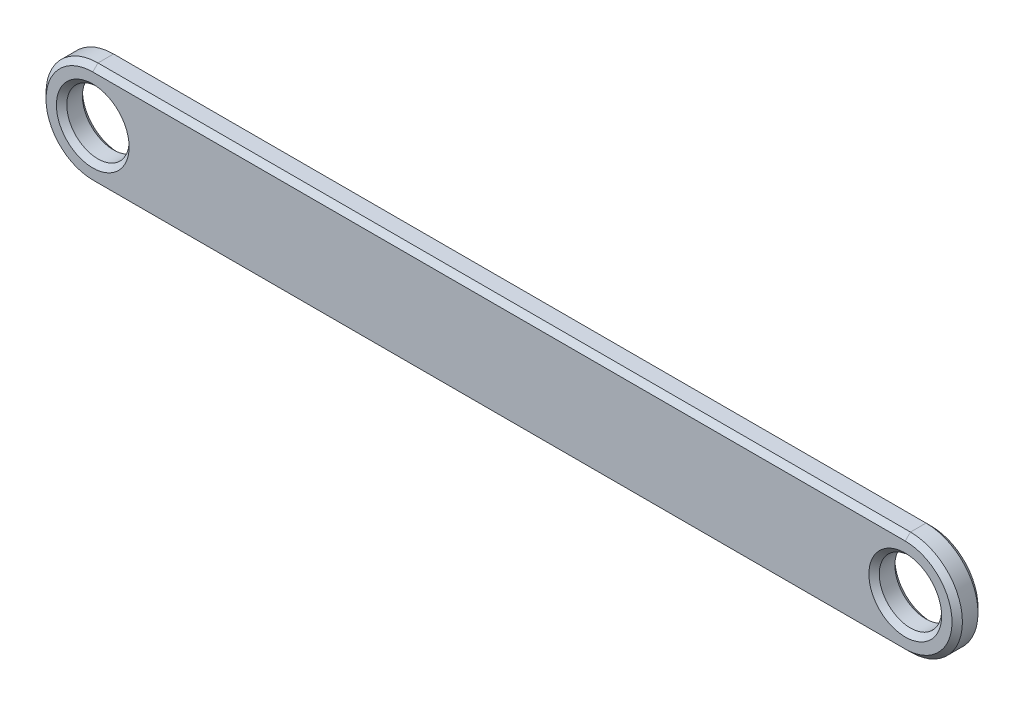
SolidWorks part; units mm, degrees
ref_plane "Front Plane" through (0, 0, 0) normal (0, 0, 1) x (1, 0, 0)
ref_plane "Top Plane" through (0, 0, 0) normal (0, 1, 0) x (1, 0, 0)
ref_plane "Right Plane" through (0, 0, 0) normal (1, 0, 0) x (0, 0, -1)
sketch "Sketch1" plane through (0, 0, 0) normal (0, 0, 1) x (1, 0, 0)
  line L0 (0, 157.4916) -> (0, -223.2358) construction
  line L1 (390.915, -50) -> (-390.915, -50)
  line L3 (390.915, 50) -> (-390.915, 50)
  line L4 (-390.915, 0) -> (390.915, 0) construction
  arc A0 (-390.915, 50) -> (-390.915, -50) centre (-390.915, 0) ccw
  circle A1 centre (-390.915, 0) radius 30
  arc A2 (390.915, 50) -> (390.915, -50) centre (390.915, 0) cw
  circle A3 centre (390.915, 0) radius 30
  point P0 (0, 0)
  dimension "D1" = 60
  dimension "D2" = 20
  dimension "D3" = 781.83
extrude "Boss-Extrude1" add sketch "Sketch1" along normal blind 25
chamfer "Chamfer1" distance 5 angle 45 12 edges at (360.915, 0, 0) (-360.915, 0, 0) (0, -50, 0) (440.915, 0, 0) (0, 50, 0) (-440.915, 0, 0) (360.915, 0, 25) (0, 50, 25) (440.915, 0, 25) (0, -50, 25) (-440.915, 0, 25) (-360.915, 0, 25)
equation "\"length\" = 781.83"
equation "\"D3@Sketch1\"=\"length\""
